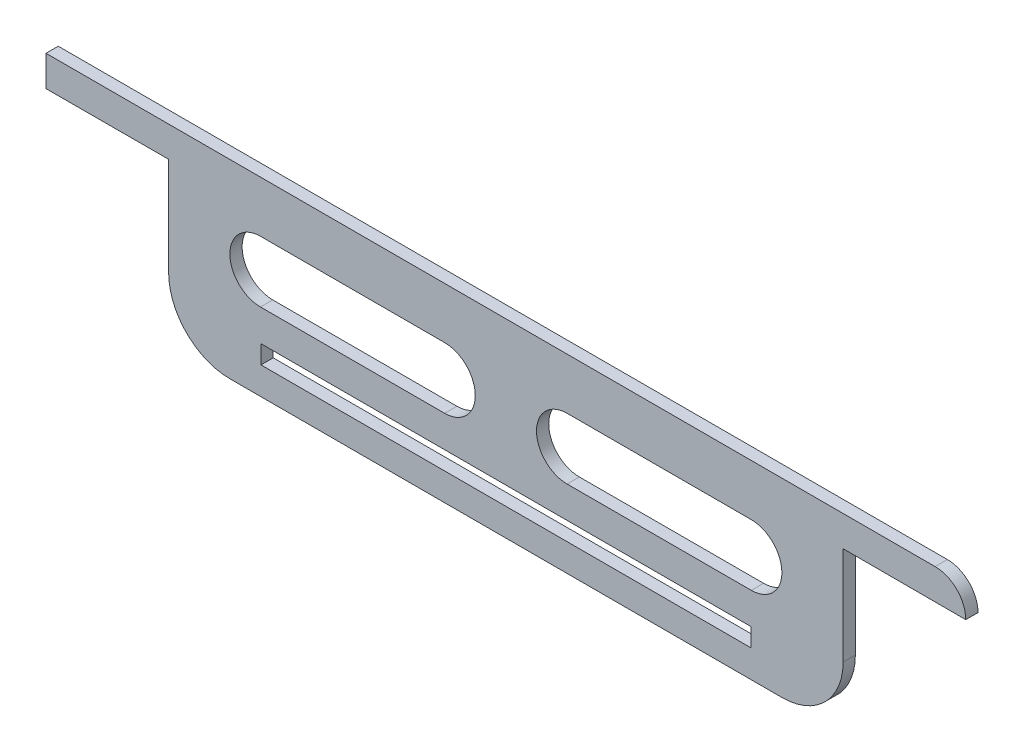
SolidWorks part; units mm, degrees
material "Hexcel AS4C (3000 Filaments)"
ref_plane "Front Plane" through (0, 0, 0) normal (0, 0, 1) x (1, 0, 0)
ref_plane "Top Plane" through (0, 0, 0) normal (0, 1, 0) x (1, 0, 0)
ref_plane "Right Plane" through (0, 0, 0) normal (1, 0, 0) x (0, 0, -1)
sketch "Sketch1" plane through (0, 0, 0) normal (0, 0, 1) x (1, 0, 0)
  line L0 (-75.1093, -2.5036) -> (-55.0802, -2.4781)
  line L2 (-75.1093, -2.5036) -> (-75.1093, -2.4964)
  line L3 (-70.1093, 2.5036) -> (70.1093, 2.5036)
  line L4 (75.1093, -2.5036) -> (75.1093, -2.4964)
  line L5 (-70.1093, 2.5036) -> (-75.1093, 2.5036)
  line L6 (-75.1093, 2.5036) -> (-75.1093, -2.5036)
  line L7 (-45.0802, -28.5219) -> (45.0802, -28.5219)
  line L8 (-55.0802, -18.5219) -> (-55.0802, -2.4781)
  line L10 (55.0802, -18.5219) -> (55.0802, -2.4781)
  line L13 (-40, -24.0219) -> (40, -24.0219)
  line L14 (-40, -24.0219) -> (-40, -21.0219)
  line L15 (-40, -21.0219) -> (40, -21.0219)
  line L16 (40, -24.0219) -> (40, -21.0219)
  line L17 (-40, -24.0219) -> (40, -21.0219) construction
  line L18 (-40, -21.0219) -> (40, -24.0219) construction
  line L19 (55.0802, -2.4781) -> (75.1093, -2.5036)
  line L26 (-40.0802, -10.8681) -> (-10, -10.8681) construction
  line L27 (-40.0802, -5.8681) -> (-10, -5.8681)
  line L28 (-40.0802, -15.8681) -> (-10, -15.8681)
  line L29 (10, -10.8681) -> (40.0802, -10.8681) construction
  line L30 (10, -5.8681) -> (40.0802, -5.8681)
  line L31 (10, -15.8681) -> (40.0802, -15.8681)
  arc A0 (45.0802, -28.5219) -> (55.0802, -18.5219) centre (45.0802, -18.5219) ccw
  arc A1 (-45.0802, -28.5219) -> (-55.0802, -18.5219) centre (-45.0802, -18.5219) cw
  arc A2 (70.1093, 2.5036) -> (75.1093, -2.4964) centre (70.1093, -2.4964) cw
  arc A4 (-40.0802, -5.8681) -> (-40.0802, -15.8681) centre (-40.0802, -10.8681) ccw
  arc A5 (-10, -15.8681) -> (-10, -5.8681) centre (-10, -10.8681) ccw
  arc A6 (10, -5.8681) -> (10, -15.8681) centre (10, -10.8681) ccw
  arc A7 (40.0802, -15.8681) -> (40.0802, -5.8681) centre (40.0802, -10.8681) ccw
  point P0 (0, 0)
  point P3 (0, -22.5219)
  point P4 (0, 0)
  point P6 (0, 0)
  point P8 (0, -17.5)
  point P29 (-25.0401, -10.8681)
  point P32 (0, -17.5)
  point P42 (25.0401, -10.8681)
  dimension "D1" = 10
  dimension "D2" = 5
extrude "Boss-Extrude1" add sketch "Sketch1" along normal blind 2
